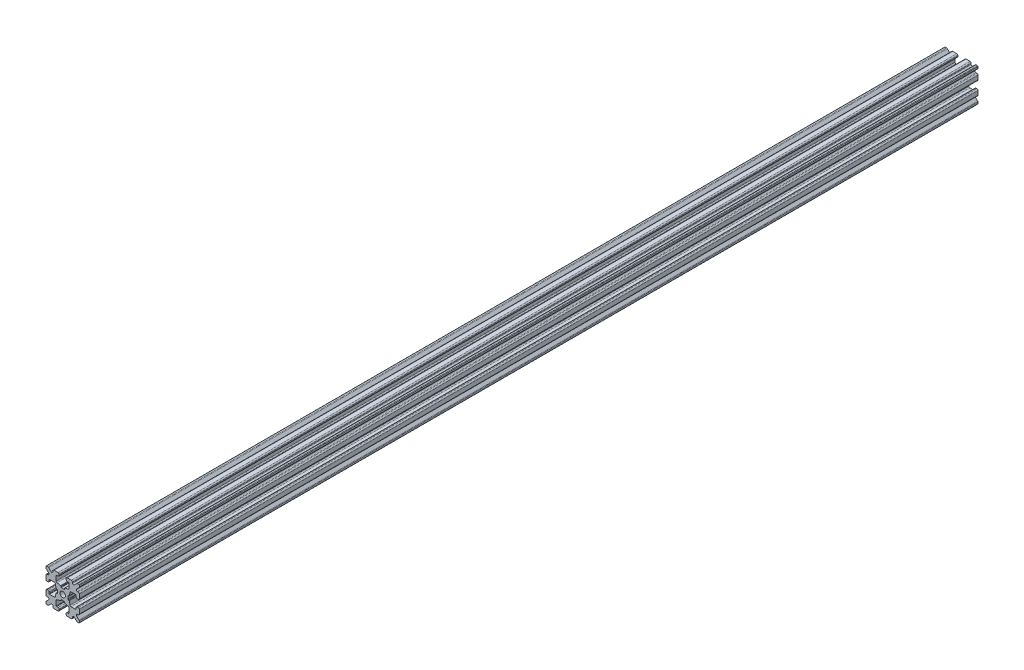
SolidWorks part; units mm, degrees
material "1060 Alloy"
ref_plane "Front Plane" through (0, 0, 0) normal (0, 0, 1) x (1, 0, 0)
ref_plane "Top Plane" through (0, 0, 0) normal (0, 1, 0) x (1, 0, 0)
ref_plane "Right Plane" through (0, 0, 0) normal (1, 0, 0) x (0, 0, -1)
sketch "Sketch1" plane through (0, 0, 0) normal (0, 0, 1) x (1, 0, 0)
  line L1 (-7.5, -7.5) -> (7.5, -7.5)
  line L2 (-7.5, -7.5) -> (-7.5, 7.5)
  line L3 (-7.5, 7.5) -> (7.5, 7.5)
  line L4 (7.5, -7.5) -> (7.5, 7.5)
  line L5 (-7.5, -7.5) -> (7.5, 7.5) construction
  line L6 (-7.5, 7.5) -> (7.5, -7.5) construction
  circle A0 centre (0, 0) radius 1.25
  point P0 (0, 0)
  dimension "D2" = 2.5
  dimension "D1" = 15
extrude "Boss-Extrude1" add sketch "Sketch1" along normal mid plane 405
fillet "Fillet1" radius 0.25 4 edges at (7.5, -7.5, 0) (-7.5, -7.5, 0) (7.5, 7.5, 0) (-7.5, 7.5, 0)
sketch "Sketch2" plane through (0, 0, 202.5) normal (0, 0, 1) x (1, 0, 0)
  line L0 (-7.5, 7.25) -> (-7.5, -7.25) construction
  line L1 (-7.5, 1.6) -> (-6.1, 1.6)
  line L2 (-7.5, 1.6) -> (-7.5, -1.6)
  line L3 (-7.5, -1.6) -> (-6.1, -1.6)
  line L4 (-6.1, 1.6) -> (-6.1, 2.9)
  line L5 (0, 0) -> (-12.1036, 0) construction
  line L6 (-6.1, -2.9) -> (-3.4, -2.9)
  line L7 (0, 0) -> (-7.25, 7.25) construction
  line L8 (-6.1, 2.9) -> (-3.4, 2.9)
  line L9 (-3.4, -2.9) -> (-3.4, 2.9)
  line L10 (55, 0) -> (-55, 0) construction
  line L11 (-6.1, -2.9) -> (-6.1, -1.6)
  line L12 (2.9, 6.1) -> (1.6, 6.1)
  line L13 (2.9, 3.4) -> (-2.9, 3.4)
  line L14 (-2.9, 6.1) -> (-2.9, 3.4)
  line L15 (2.9, 6.1) -> (2.9, 3.4)
  line L16 (-1.6, 6.1) -> (-2.9, 6.1)
  line L17 (1.6, 7.5) -> (1.6, 6.1)
  line L18 (-1.6, 7.5) -> (1.6, 7.5)
  line L19 (-1.6, 7.5) -> (-1.6, 6.1)
  line L20 (-1.6, -7.5) -> (-1.6, -6.1)
  line L21 (-1.6, -7.5) -> (1.6, -7.5)
  line L22 (1.6, -7.5) -> (1.6, -6.1)
  line L23 (-1.6, -6.1) -> (-2.9, -6.1)
  line L24 (2.9, -6.1) -> (2.9, -3.4)
  line L25 (-2.9, -6.1) -> (-2.9, -3.4)
  line L26 (2.9, -3.4) -> (-2.9, -3.4)
  line L27 (2.9, -6.1) -> (1.6, -6.1)
  line L28 (6.1, -2.9) -> (6.1, -1.6)
  line L29 (3.4, -2.9) -> (3.4, 2.9)
  line L30 (6.1, 2.9) -> (3.4, 2.9)
  line L31 (6.1, -2.9) -> (3.4, -2.9)
  line L32 (6.1, 1.6) -> (6.1, 2.9)
  line L33 (7.5, -1.6) -> (6.1, -1.6)
  line L34 (7.5, 1.6) -> (7.5, -1.6)
  line L35 (7.5, 1.6) -> (6.1, 1.6)
  dimension "D1" = 3.2
  dimension "D2" = 5.8
  dimension "D3" = 1.4
  dimension "D4" = 2.7
extrude "Cut-Extrude1" cut sketch "Sketch2" against normal through all
sketch "Sketch4" plane through (0, 0, 202.5) normal (0, 0, 1) x (1, 0, 0)
  line L0 (-3.4, 2.9) -> (-2.75, 0)
  line L1 (55, 0) -> (-55, 0) construction
  line L2 (-2.75, 0) -> (-3.4, -2.9)
  line L3 (-3.4, -2.9) -> (-3.4, 2.9) construction
  line L4 (-3.4, 2.9) -> (-3.4, -2.9)
  line L5 (-2.9, 3.4) -> (0, 2.75)
  line L6 (0, 2.75) -> (2.9, 3.4)
  line L7 (2.9, 3.4) -> (-2.9, 3.4)
  line L8 (3.4, 2.9) -> (2.75, 0)
  line L9 (2.75, 0) -> (3.4, -2.9)
  line L10 (3.4, -2.9) -> (3.4, 2.9)
  line L11 (-2.9, -3.4) -> (0, -2.75)
  line L12 (0, -2.75) -> (2.9, -3.4)
  line L13 (2.9, -3.4) -> (-2.9, -3.4)
  circle A2 centre (0, 0) radius 2.75
  circle A3 centre (0, 0) radius 2.75 construction
  dimension "D1" = 1.5
extrude "Cut-Extrude3" cut sketch "Sketch4" against normal through all
fillet "Fillet3" radius 0.5 16 edges at (-6.1, -1.6, 0) (-7.5, -1.6, 0) (-6.1, 1.6, 0) (-7.5, 1.6, 0) (-1.6, -7.5, 0) (-1.6, -6.1, 0) (1.6, -7.5, 0) (1.6, -6.1, 0) (6.1, -1.6, 0) (7.5, -1.6, 0) (7.5, 1.6, 0) (6.1, 1.6, 0) (1.6, 7.5, 0) (1.6, 6.1, 0) (-1.6, 7.5, 0) (-1.6, 6.1, 0)
fillet "Fillet4" radius 0.5 8 edges at (-3.4, 2.9, 0) (-3.4, -2.9, 0) (2.9, -3.4, 0) (-2.9, -3.4, 0) (3.4, -2.9, 0) (3.4, 2.9, 0) (-2.9, 3.4, 0) (2.9, 3.4, 0)
fillet "Fillet5" radius 3 4 edges at (0, -2.75, 0) (2.75, 0, 0) (-2.75, 0, 0) (0, 2.75, 0)
fillet "Fillet6" radius 0.2 8 edges at (-2.9, -6.1, 0) (2.9, -6.1, 0) (6.1, -2.9, 0) (6.1, 2.9, 0) (2.9, 6.1, 0) (-2.9, 6.1, 0) (-6.1, -2.9, 0) (-6.1, 2.9, 0)
sketch "Sketch5" plane through (0, 0, 202.5) normal (0, 0, 1) x (1, 0, 0)
  line L0 (0, 0) -> (-7.25, 7.25) construction
  line L1 (-7.5, 6.4393) -> (-5.4607, 4.4)
  line L2 (-6.4393, 7.5) -> (-4.4, 5.4607)
  line L3 (-7.5, 4.4) -> (-5.4607, 4.4)
  line L4 (-3.8003, 2.9) -> (-5.9, 2.9) construction
  line L5 (0, 0) -> (-12.1819, 0) construction
  line L6 (-4.4, 7.5) -> (-4.4, 5.4607)
  line L7 (-2.9, 5.9) -> (-2.9, 3.8003) construction
  line L8 (-7.5, 6.4393) -> (-7.5, 4.4)
  line L9 (-7.5, 7.25) -> (-7.5, 2.1) construction
  line L10 (2.1, -7.5) -> (7.25, -7.5) construction
  line L11 (7.5, -7.25) -> (7.5, -2.1) construction
  line L12 (7.25, 7.5) -> (2.1, 7.5) construction
  line L13 (-2.1, 7.5) -> (-7.25, 7.5) construction
  line L14 (-4.4, 7.5) -> (-6.4393, 7.5)
  line L16 (55, 0) -> (-55, 0) construction
  line L17 (0, 0) -> (0, 10.993) construction
  line L18 (0, -54.6431) -> (0, 54.6431) construction
  line L20 (4.4, 7.5) -> (6.4393, 7.5)
  line L22 (7.5, 6.4393) -> (7.5, 4.4)
  line L23 (4.4, 7.5) -> (4.4, 5.4607)
  line L24 (7.5, 4.4) -> (5.4607, 4.4)
  line L25 (6.4393, 7.5) -> (4.4, 5.4607)
  line L26 (7.5, 6.4393) -> (5.4607, 4.4)
  line L27 (7.5, -6.4393) -> (5.4607, -4.4)
  line L28 (6.4393, -7.5) -> (4.4, -5.4607)
  line L29 (7.5, -4.4) -> (5.4607, -4.4)
  line L30 (4.4, -7.5) -> (4.4, -5.4607)
  line L31 (7.5, -6.4393) -> (7.5, -4.4)
  line L33 (4.4, -7.5) -> (6.4393, -7.5)
  line L36 (-4.4, -7.5) -> (-6.4393, -7.5)
  line L38 (-7.5, -6.4393) -> (-7.5, -4.4)
  line L39 (-4.4, -7.5) -> (-4.4, -5.4607)
  line L40 (-7.5, -4.4) -> (-5.4607, -4.4)
  line L41 (-6.4393, -7.5) -> (-4.4, -5.4607)
  line L42 (-7.5, -6.4393) -> (-5.4607, -4.4)
  dimension "D1" = 1.5
  dimension "D2" = 1.5
  dimension "D3" = 1.5
extrude "Cut-Extrude4" cut sketch "Sketch5" against normal through all
fillet "Fillet8" radius 0.5 24 edges at (-5.4607, 4.4, 0) (-7.5, 4.4, 0) (-5.4607, -4.4, 0) (-7.5, -4.4, 0) (-4.4, -7.5, 0) (-4.4, -5.4607, 0) (4.4, -7.5, 0) (4.4, -5.4607, 0) (5.4607, -4.4, 0) (7.5, -4.4, 0) (7.5, 4.4, 0) (5.4607, 4.4, 0) (4.4, 5.4607, 0) (4.4, 7.5, 0) (-4.4, 5.4607, 0) (-4.4, 7.5, 0) (-6.4393, 7.5, 0) (-7.5, 6.4393, 0) (6.4393, 7.5, 0) (7.5, 6.4393, 0) (6.4393, -7.5, 0) (7.5, -6.4393, 0) (-6.4393, -7.5, 0) (-7.5, -6.4393, 0)
sketch "Sketch6" plane through (0, 0, 202.5) normal (0, 0, 1) x (1, 0, 0)
  line L0 (0, 0) -> (0, 11.013) construction
  line L1 (0.6561, 2.8971) -> (2.1235, 2.8971) construction
  line L2 (0, -54.6431) -> (0, 54.6431) construction
  line L3 (0, 0) -> (7.25, 7.25) construction
  line L4 (7.5, 0.8255) -> (7.5, -0.8255)
  line L5 (2.3471, 0.8255) -> (7.5, 0.8255)
  line L6 (0, 0) -> (12.4016, 0) construction
  line L7 (0.8255, -7.5) -> (-0.8255, -7.5)
  line L8 (2.3471, -0.8255) -> (2.3471, 0.8255)
  line L9 (0.8255, -2.3471) -> (0.8255, -7.5)
  line L10 (7.5, -0.8255) -> (2.3471, -0.8255)
  line L11 (-7.5, -0.8255) -> (-2.3471, -0.8255)
  line L12 (-2.3471, -0.8255) -> (-2.3471, 0.8255)
  line L13 (-0.8255, -2.3471) -> (0.8255, -2.3471)
  line L14 (-0.8255, 7.5) -> (-0.8255, 2.3471)
  line L15 (-0.8255, 2.3471) -> (0.8255, 2.3471)
  line L16 (-0.8255, -7.5) -> (-0.8255, -2.3471)
  line L17 (0.8255, 2.3471) -> (0.8255, 7.5)
  line L18 (0.8255, 7.5) -> (-0.8255, 7.5)
  line L19 (3.9, 7.5) -> (2.1, 7.5) construction
  line L20 (-2.3471, 0.8255) -> (-7.5, 0.8255)
  line L21 (-7.5, 0.8255) -> (-7.5, -0.8255)
  point P5 (0, -2.5973)
  point P7 (0, 2.5973)
  dimension "D3" = 0.55
  dimension "D1" = 1.651
extrude "Cut-Extrude5" cut sketch "Sketch6" against normal through all
fillet "Fillet10" radius 0.2 16 edges at (-2.935, 0.8255, 0) (-2.935, -0.8255, 0) (2.935, -0.8255, 0) (2.935, 0.8255, 0) (0.8255, 2.935, 0) (-0.8255, 2.935, 0) (-2.3471, 0.8255, 0) (-2.3471, -0.8255, 0) (0.8255, 2.3471, 0) (-0.8255, 2.3471, 0) (2.3471, 0.8255, 0) (2.3471, -0.8255, 0) (0.8255, -2.935, 0) (0.8255, -2.3471, 0) (-0.8255, -2.3471, 0) (-0.8255, -2.935, 0)
